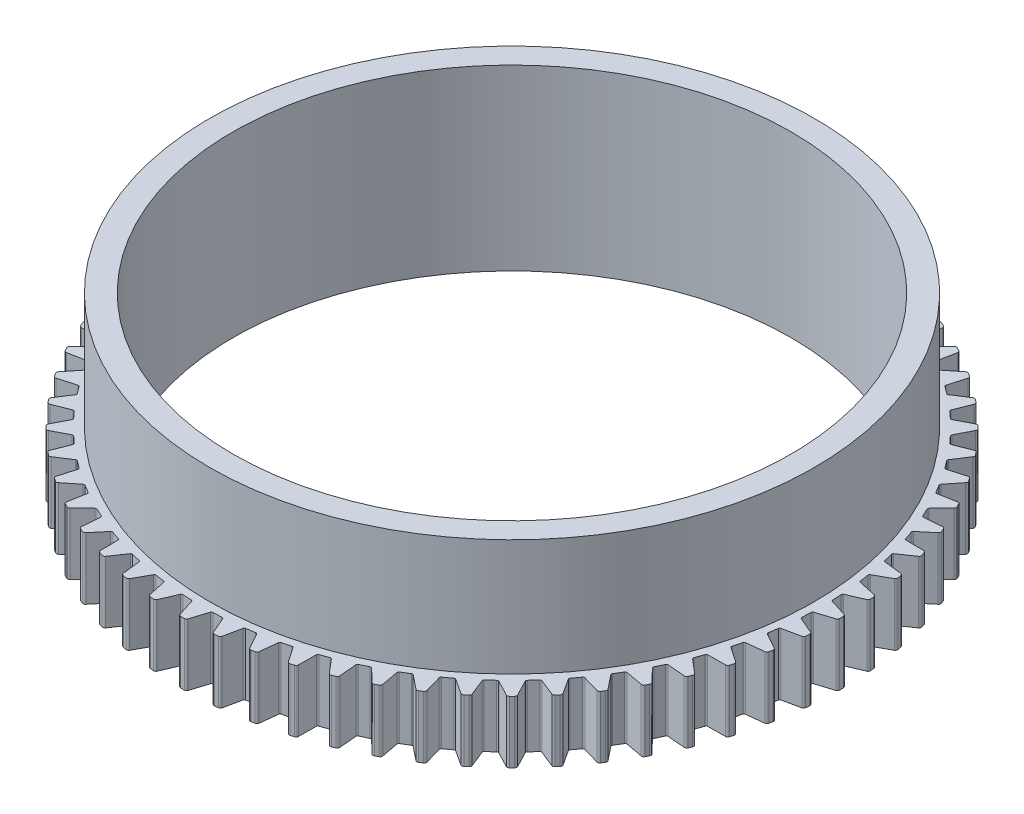
SolidWorks part; units mm, degrees
ref_plane "Front Plane" through (0, 0, 0) normal (0, 0, 1) x (1, 0, 0)
ref_plane "Top Plane" through (0, 0, 0) normal (0, 1, 0) x (1, 0, 0)
ref_plane "Right Plane" through (0, 0, 0) normal (1, 0, 0) x (0, 0, -1)
sketch "Sketch1" plane through (0, 0, 0) normal (0, 1, 0) x (1, 0, 0)
  line L0 (0, 53.7167) -> (0, -50.4595) construction
  line L1 (-0.5164, 42.2908) -> (-1.2072, 40.1152)
  line L2 (-0.2305, 42.5) -> (0.2305, 42.5)
  line L3 (0.5164, 42.2908) -> (1.2072, 40.1152)
  line L4 (3.6313, 42.1378) -> (2.7306, 40.0403)
  line L5 (4.6592, 42.0365) -> (5.1334, 39.8037)
  line L6 (3.9363, 42.3179) -> (4.3951, 42.2728)
  line L7 (7.744, 41.5789) -> (6.642, 39.5799)
  line L8 (8.757, 41.3774) -> (9.0101, 39.1088)
  line L9 (8.0653, 41.7283) -> (8.5174, 41.6384)
  line L10 (11.7822, 40.6197) -> (10.4896, 38.7383)
  line L11 (12.7706, 40.3199) -> (12.8001, 38.0374)
  line L12 (12.1165, 40.7369) -> (12.5577, 40.6031)
  line L13 (15.7069, 39.2692) -> (14.2361, 37.5236)
  line L14 (16.6611, 38.874) -> (16.4667, 36.5996)
  line L15 (16.0511, 39.3531) -> (16.477, 39.1767)
  line L16 (19.4803, 37.5406) -> (17.8455, 35.9475)
  line L17 (20.3912, 37.0537) -> (19.9748, 34.8093)
  line L18 (19.8311, 37.5903) -> (20.2376, 37.373)
  line L19 (23.0661, 35.4504) -> (21.283, 34.0252)
  line L20 (23.9249, 34.8766) -> (23.2906, 32.6838)
  line L21 (23.4201, 35.4655) -> (23.8034, 35.2094)
  line L22 (26.4298, 33.0188) -> (24.5156, 31.7753)
  line L23 (27.2282, 32.3636) -> (26.382, 30.2436)
  line L24 (26.7835, 32.9992) -> (27.1399, 32.7067)
  line L25 (29.5389, 30.2693) -> (27.5121, 29.2193)
  line L26 (30.2693, 29.5389) -> (29.2193, 27.5121)
  line L27 (29.8891, 30.215) -> (30.215, 29.8891)
  line L28 (32.3636, 27.2282) -> (30.2436, 26.382)
  line L29 (33.0188, 26.4298) -> (31.7753, 24.5156)
  line L30 (32.7067, 27.1399) -> (32.9992, 26.7835)
  line L31 (34.8766, 23.9249) -> (32.6838, 23.2906)
  line L32 (35.4504, 23.0661) -> (34.0252, 21.283)
  line L33 (35.2094, 23.8034) -> (35.4655, 23.4201)
  line L34 (37.0537, 20.3912) -> (34.8093, 19.9748)
  line L35 (37.5406, 19.4803) -> (35.9475, 17.8455)
  line L36 (37.373, 20.2376) -> (37.5903, 19.8311)
  line L37 (38.874, 16.6611) -> (36.5996, 16.4667)
  line L38 (39.2692, 15.7069) -> (37.5236, 14.2361)
  line L39 (39.1767, 16.477) -> (39.3531, 16.0511)
  line L40 (40.3199, 12.7706) -> (38.0374, 12.8001)
  line L41 (40.6197, 11.7822) -> (38.7383, 10.4896)
  line L42 (40.6031, 12.5577) -> (40.7369, 12.1165)
  line L43 (41.3774, 8.757) -> (39.1088, 9.0101)
  line L44 (41.5789, 7.744) -> (39.5799, 6.642)
  line L45 (41.6384, 8.5174) -> (41.7283, 8.0653)
  line L46 (42.0365, 4.6592) -> (39.8037, 5.1334)
  line L47 (42.1378, 3.6313) -> (40.0403, 2.7306)
  line L48 (42.2728, 4.3951) -> (42.3179, 3.9363)
  line L49 (42.2908, 0.5164) -> (40.1152, 1.2072)
  line L50 (42.2908, -0.5164) -> (40.1152, -1.2072)
  line L51 (42.5, 0.2305) -> (42.5, -0.2305)
  line L52 (42.1378, -3.6313) -> (40.0403, -2.7306)
  line L53 (42.0365, -4.6592) -> (39.8037, -5.1334)
  line L54 (42.3179, -3.9363) -> (42.2728, -4.3951)
  line L55 (41.5789, -7.744) -> (39.5799, -6.642)
  line L56 (41.3774, -8.757) -> (39.1088, -9.0101)
  line L57 (41.7283, -8.0653) -> (41.6384, -8.5174)
  line L58 (40.6197, -11.7822) -> (38.7383, -10.4896)
  line L59 (40.3199, -12.7706) -> (38.0374, -12.8001)
  line L60 (40.7369, -12.1165) -> (40.6031, -12.5577)
  line L61 (39.2692, -15.7069) -> (37.5236, -14.2361)
  line L62 (38.874, -16.6611) -> (36.5996, -16.4667)
  line L63 (39.3531, -16.0511) -> (39.1767, -16.477)
  line L64 (37.5406, -19.4803) -> (35.9475, -17.8455)
  line L65 (37.0537, -20.3912) -> (34.8093, -19.9748)
  line L66 (37.5903, -19.8311) -> (37.373, -20.2376)
  line L67 (35.4504, -23.0661) -> (34.0252, -21.283)
  line L68 (34.8766, -23.9249) -> (32.6838, -23.2906)
  line L69 (35.4655, -23.4201) -> (35.2094, -23.8034)
  line L70 (33.0188, -26.4298) -> (31.7753, -24.5156)
  line L71 (32.3636, -27.2282) -> (30.2436, -26.382)
  line L72 (32.9992, -26.7835) -> (32.7067, -27.1399)
  line L73 (30.2693, -29.5389) -> (29.2193, -27.5121)
  line L74 (29.5389, -30.2693) -> (27.5121, -29.2193)
  line L75 (30.215, -29.8891) -> (29.8891, -30.215)
  line L76 (27.2282, -32.3636) -> (26.382, -30.2436)
  line L77 (26.4298, -33.0188) -> (24.5156, -31.7753)
  line L78 (27.1399, -32.7067) -> (26.7835, -32.9992)
  line L79 (23.9249, -34.8766) -> (23.2906, -32.6838)
  line L80 (23.0661, -35.4504) -> (21.283, -34.0252)
  line L81 (23.8034, -35.2094) -> (23.4201, -35.4655)
  line L82 (20.3912, -37.0537) -> (19.9748, -34.8093)
  line L83 (19.4803, -37.5406) -> (17.8455, -35.9475)
  line L84 (20.2376, -37.373) -> (19.8311, -37.5903)
  line L85 (16.6611, -38.874) -> (16.4667, -36.5996)
  line L86 (15.7069, -39.2692) -> (14.2361, -37.5236)
  line L87 (16.477, -39.1767) -> (16.0511, -39.3531)
  line L88 (12.7706, -40.3199) -> (12.8001, -38.0374)
  line L89 (11.7822, -40.6197) -> (10.4896, -38.7383)
  line L90 (12.5577, -40.6031) -> (12.1165, -40.7369)
  line L91 (8.757, -41.3774) -> (9.0101, -39.1088)
  line L92 (7.744, -41.5789) -> (6.642, -39.5799)
  line L93 (8.5174, -41.6384) -> (8.0653, -41.7283)
  line L94 (4.6592, -42.0365) -> (5.1334, -39.8037)
  line L95 (3.6313, -42.1378) -> (2.7306, -40.0403)
  line L96 (4.3951, -42.2728) -> (3.9363, -42.3179)
  line L97 (0.5164, -42.2908) -> (1.2072, -40.1152)
  line L98 (-0.5164, -42.2908) -> (-1.2072, -40.1152)
  line L99 (0.2305, -42.5) -> (-0.2305, -42.5)
  line L100 (-3.6313, -42.1378) -> (-2.7306, -40.0403)
  line L101 (-4.6592, -42.0365) -> (-5.1334, -39.8037)
  line L102 (-3.9363, -42.3179) -> (-4.3951, -42.2728)
  line L103 (-7.744, -41.5789) -> (-6.642, -39.5799)
  line L104 (-8.757, -41.3774) -> (-9.0101, -39.1088)
  line L105 (-8.0653, -41.7283) -> (-8.5174, -41.6384)
  line L106 (-11.7822, -40.6197) -> (-10.4896, -38.7383)
  line L107 (-12.7706, -40.3199) -> (-12.8001, -38.0374)
  line L108 (-12.1165, -40.7369) -> (-12.5577, -40.6031)
  line L109 (-15.7069, -39.2692) -> (-14.2361, -37.5236)
  line L110 (-16.6611, -38.874) -> (-16.4667, -36.5996)
  line L111 (-16.0511, -39.3531) -> (-16.477, -39.1767)
  line L112 (-19.4803, -37.5406) -> (-17.8455, -35.9475)
  line L113 (-20.3912, -37.0537) -> (-19.9748, -34.8093)
  line L114 (-19.8311, -37.5903) -> (-20.2376, -37.373)
  line L115 (-23.0661, -35.4504) -> (-21.283, -34.0252)
  line L116 (-23.9249, -34.8766) -> (-23.2906, -32.6838)
  line L117 (-23.4201, -35.4655) -> (-23.8034, -35.2094)
  line L118 (-26.4298, -33.0188) -> (-24.5156, -31.7753)
  line L119 (-27.2282, -32.3636) -> (-26.382, -30.2436)
  line L120 (-26.7835, -32.9992) -> (-27.1399, -32.7067)
  line L121 (-29.5389, -30.2693) -> (-27.5121, -29.2193)
  line L122 (-30.2693, -29.5389) -> (-29.2193, -27.5121)
  line L123 (-29.8891, -30.215) -> (-30.215, -29.8891)
  line L124 (-32.3636, -27.2282) -> (-30.2436, -26.382)
  line L125 (-33.0188, -26.4298) -> (-31.7753, -24.5156)
  line L126 (-32.7067, -27.1399) -> (-32.9992, -26.7835)
  line L127 (-34.8766, -23.9249) -> (-32.6838, -23.2906)
  line L128 (-35.4504, -23.0661) -> (-34.0252, -21.283)
  line L129 (-35.2094, -23.8034) -> (-35.4655, -23.4201)
  line L130 (-37.0537, -20.3912) -> (-34.8093, -19.9748)
  line L131 (-37.5406, -19.4803) -> (-35.9475, -17.8455)
  line L132 (-37.373, -20.2376) -> (-37.5903, -19.8311)
  line L133 (-38.874, -16.6611) -> (-36.5996, -16.4667)
  line L134 (-39.2692, -15.7069) -> (-37.5236, -14.2361)
  line L135 (-39.1767, -16.477) -> (-39.3531, -16.0511)
  line L136 (-40.3199, -12.7706) -> (-38.0374, -12.8001)
  line L137 (-40.6197, -11.7822) -> (-38.7383, -10.4896)
  line L138 (-40.6031, -12.5577) -> (-40.7369, -12.1165)
  line L139 (-41.3774, -8.757) -> (-39.1088, -9.0101)
  line L140 (-41.5789, -7.744) -> (-39.5799, -6.642)
  line L141 (-41.6384, -8.5174) -> (-41.7283, -8.0653)
  line L142 (-42.0365, -4.6592) -> (-39.8037, -5.1334)
  line L143 (-42.1378, -3.6313) -> (-40.0403, -2.7306)
  line L144 (-42.2728, -4.3951) -> (-42.3179, -3.9363)
  line L145 (-42.2908, -0.5164) -> (-40.1152, -1.2072)
  line L146 (-42.2908, 0.5164) -> (-40.1152, 1.2072)
  line L147 (-42.5, -0.2305) -> (-42.5, 0.2305)
  line L148 (-42.1378, 3.6313) -> (-40.0403, 2.7306)
  line L149 (-42.0365, 4.6592) -> (-39.8037, 5.1334)
  line L150 (-42.3179, 3.9363) -> (-42.2728, 4.3951)
  line L151 (-41.5789, 7.744) -> (-39.5799, 6.642)
  line L152 (-41.3774, 8.757) -> (-39.1088, 9.0101)
  line L153 (-41.7283, 8.0653) -> (-41.6384, 8.5174)
  line L154 (-40.6197, 11.7822) -> (-38.7383, 10.4896)
  line L155 (-40.3199, 12.7706) -> (-38.0374, 12.8001)
  line L156 (-40.7369, 12.1165) -> (-40.6031, 12.5577)
  line L157 (-39.2692, 15.7069) -> (-37.5236, 14.2361)
  line L158 (-38.874, 16.6611) -> (-36.5996, 16.4667)
  line L159 (-39.3531, 16.0511) -> (-39.1767, 16.477)
  line L160 (-37.5406, 19.4803) -> (-35.9475, 17.8455)
  line L161 (-37.0537, 20.3912) -> (-34.8093, 19.9748)
  line L162 (-37.5903, 19.8311) -> (-37.373, 20.2376)
  line L163 (-35.4504, 23.0661) -> (-34.0252, 21.283)
  line L164 (-34.8766, 23.9249) -> (-32.6838, 23.2906)
  line L165 (-35.4655, 23.4201) -> (-35.2094, 23.8034)
  line L166 (-33.0188, 26.4298) -> (-31.7753, 24.5156)
  line L167 (-32.3636, 27.2282) -> (-30.2436, 26.382)
  line L168 (-32.9992, 26.7835) -> (-32.7067, 27.1399)
  line L169 (-30.2693, 29.5389) -> (-29.2193, 27.5121)
  line L170 (-29.5389, 30.2693) -> (-27.5121, 29.2193)
  line L171 (-30.215, 29.8891) -> (-29.8891, 30.215)
  line L172 (-27.2282, 32.3636) -> (-26.382, 30.2436)
  line L173 (-26.4298, 33.0188) -> (-24.5156, 31.7753)
  line L174 (-27.1399, 32.7067) -> (-26.7835, 32.9992)
  line L175 (-23.9249, 34.8766) -> (-23.2906, 32.6838)
  line L176 (-23.0661, 35.4504) -> (-21.283, 34.0252)
  line L177 (-23.8034, 35.2094) -> (-23.4201, 35.4655)
  line L178 (-20.3912, 37.0537) -> (-19.9748, 34.8093)
  line L179 (-19.4803, 37.5406) -> (-17.8455, 35.9475)
  line L180 (-20.2376, 37.373) -> (-19.8311, 37.5903)
  line L181 (-16.6611, 38.874) -> (-16.4667, 36.5996)
  line L182 (-15.7069, 39.2692) -> (-14.2361, 37.5236)
  line L183 (-16.477, 39.1767) -> (-16.0511, 39.3531)
  line L184 (-12.7706, 40.3199) -> (-12.8001, 38.0374)
  line L185 (-11.7822, 40.6197) -> (-10.4896, 38.7383)
  line L186 (-12.5577, 40.6031) -> (-12.1165, 40.7369)
  line L187 (-8.757, 41.3774) -> (-9.0101, 39.1088)
  line L188 (-7.744, 41.5789) -> (-6.642, 39.5799)
  line L189 (-8.5174, 41.6384) -> (-8.0653, 41.7283)
  line L190 (-4.6592, 42.0365) -> (-5.1334, 39.8037)
  line L191 (-3.6313, 42.1378) -> (-2.7306, 40.0403)
  line L192 (-4.3951, 42.2728) -> (-3.9363, 42.3179)
  arc A0 (-1.3909, 39.9758) -> (-2.5341, 39.9196) centre (0, 0) ccw
  arc A1 (-0.5164, 42.2908) -> (-0.2305, 42.5) centre (-0.2305, 42.2) cw
  arc A2 (0.2305, 42.5) -> (0.5164, 42.2908) centre (0.2305, 42.2) cw
  arc A3 (1.2072, 40.1152) -> (1.3909, 39.9758) centre (1.3979, 40.1757) ccw
  arc A4 (-1.2072, 40.1152) -> (-1.3909, 39.9758) centre (-1.3979, 40.1757) cw
  arc A5 (2.7306, 40.0403) -> (2.5341, 39.9196) centre (2.5468, 40.1192) cw
  arc A6 (5.1334, 39.8037) -> (5.3025, 39.647) centre (5.329, 39.8452) ccw
  arc A7 (4.3951, 42.2728) -> (4.6592, 42.0365) centre (4.3657, 41.9742) cw
  arc A8 (3.6313, 42.1378) -> (3.9363, 42.3179) centre (3.9069, 42.0194) cw
  arc A9 (6.642, 39.5799) -> (6.4347, 39.479) centre (6.4669, 39.6764) cw
  arc A10 (9.0101, 39.1088) -> (9.1631, 38.9363) centre (9.2089, 39.131) ccw
  arc A11 (8.5174, 41.6384) -> (8.757, 41.3774) centre (8.4589, 41.3442) cw
  arc A12 (7.744, 41.5789) -> (8.0653, 41.7283) centre (8.0067, 41.4341) cw
  arc A13 (10.4896, 38.7383) -> (10.2734, 38.6582) centre (10.3247, 38.8515) cw
  arc A14 (12.8001, 38.0374) -> (12.9354, 37.8507) centre (13, 38.04) ccw
  arc A15 (12.5577, 40.6031) -> (12.7706, 40.3199) centre (12.4706, 40.316) cw
  arc A16 (11.7822, 40.6197) -> (12.1165, 40.7369) centre (12.0294, 40.4498) cw
  arc A17 (14.2361, 37.5236) -> (14.0131, 37.4651) centre (14.0831, 37.6524) cw
  arc A18 (16.4667, 36.5996) -> (16.5831, 36.4006) centre (16.666, 36.5826) ccw
  arc A19 (16.477, 39.1767) -> (16.6611, 38.874) centre (16.3622, 38.8995) cw
  arc A20 (15.7069, 39.2692) -> (16.0511, 39.3531) centre (15.9363, 39.0759) cw
  arc A21 (17.8455, 35.9475) -> (17.6178, 35.9112) centre (17.7059, 36.0907) cw
  arc A22 (19.9748, 34.8093) -> (20.0711, 34.5999) centre (20.1715, 34.7729) ccw
  arc A23 (20.2376, 37.373) -> (20.3912, 37.0537) centre (20.0962, 37.1084) cw
  arc A24 (19.4803, 37.5406) -> (19.8311, 37.5903) centre (19.6897, 37.3257) cw
  arc A25 (21.283, 34.0252) -> (21.0529, 34.0114) centre (21.1581, 34.1815) cw
  arc A26 (23.2906, 32.6838) -> (23.3659, 32.4659) centre (23.4827, 32.6283) ccw
  arc A27 (23.8034, 35.2094) -> (23.9249, 34.8766) centre (23.6367, 34.96) cw
  arc A28 (23.0661, 35.4504) -> (23.4201, 35.4655) centre (23.2534, 35.2161) cw
  arc A29 (24.5156, 31.7753) -> (24.2852, 31.7841) centre (24.4066, 31.943) cw
  arc A30 (26.382, 30.2436) -> (26.4356, 30.0193) centre (26.5677, 30.1694) ccw
  arc A31 (27.1399, 32.7067) -> (27.2282, 32.3636) centre (26.9496, 32.4748) cw
  arc A32 (26.4298, 33.0188) -> (26.7835, 32.9992) centre (26.5932, 32.7673) cw
  arc A33 (27.5121, 29.2193) -> (27.2837, 29.2507) centre (27.4201, 29.3969) cw
  arc A34 (29.2193, 27.5121) -> (29.2507, 27.2837) centre (29.3969, 27.4201) ccw
  arc A35 (30.215, 29.8891) -> (30.2693, 29.5389) centre (30.0029, 29.6769) cw
  arc A36 (29.5389, 30.2693) -> (29.8891, 30.215) centre (29.6769, 30.0029) cw
  arc A37 (30.2436, 26.382) -> (30.0193, 26.4356) centre (30.1694, 26.5677) cw
  arc A38 (31.7753, 24.5156) -> (31.7841, 24.2852) centre (31.943, 24.4066) ccw
  arc A39 (32.9992, 26.7835) -> (33.0188, 26.4298) centre (32.7673, 26.5932) cw
  arc A40 (32.3636, 27.2282) -> (32.7067, 27.1399) centre (32.4748, 26.9496) cw
  arc A41 (32.6838, 23.2906) -> (32.4659, 23.3659) centre (32.6283, 23.4827) cw
  arc A42 (34.0252, 21.283) -> (34.0114, 21.0529) centre (34.1815, 21.1581) ccw
  arc A43 (35.4655, 23.4201) -> (35.4504, 23.0661) centre (35.2161, 23.2534) cw
  arc A44 (34.8766, 23.9249) -> (35.2094, 23.8034) centre (34.96, 23.6367) cw
  arc A45 (34.8093, 19.9748) -> (34.5999, 20.0711) centre (34.7729, 20.1715) cw
  arc A46 (35.9475, 17.8455) -> (35.9112, 17.6178) centre (36.0907, 17.7059) ccw
  arc A47 (37.5903, 19.8311) -> (37.5406, 19.4803) centre (37.3257, 19.6897) cw
  arc A48 (37.0537, 20.3912) -> (37.373, 20.2376) centre (37.1084, 20.0962) cw
  arc A49 (36.5996, 16.4667) -> (36.4006, 16.5831) centre (36.5826, 16.666) cw
  arc A50 (37.5236, 14.2361) -> (37.4651, 14.0131) centre (37.6524, 14.0831) ccw
  arc A51 (39.3531, 16.0511) -> (39.2692, 15.7069) centre (39.0759, 15.9363) cw
  arc A52 (38.874, 16.6611) -> (39.1767, 16.477) centre (38.8995, 16.3622) cw
  arc A53 (38.0374, 12.8001) -> (37.8507, 12.9354) centre (38.04, 13) cw
  arc A54 (38.7383, 10.4896) -> (38.6582, 10.2734) centre (38.8515, 10.3247) ccw
  arc A55 (40.7369, 12.1165) -> (40.6197, 11.7822) centre (40.4498, 12.0294) cw
  arc A56 (40.3199, 12.7706) -> (40.6031, 12.5577) centre (40.316, 12.4706) cw
  arc A57 (39.1088, 9.0101) -> (38.9363, 9.1631) centre (39.131, 9.2089) cw
  arc A58 (39.5799, 6.642) -> (39.479, 6.4347) centre (39.6764, 6.4669) ccw
  arc A59 (41.7283, 8.0653) -> (41.5789, 7.744) centre (41.4341, 8.0067) cw
  arc A60 (41.3774, 8.757) -> (41.6384, 8.5174) centre (41.3442, 8.4589) cw
  arc A61 (39.8037, 5.1334) -> (39.647, 5.3025) centre (39.8452, 5.329) cw
  arc A62 (40.0403, 2.7306) -> (39.9196, 2.5341) centre (40.1192, 2.5468) ccw
  arc A63 (42.3179, 3.9363) -> (42.1378, 3.6313) centre (42.0194, 3.9069) cw
  arc A64 (42.0365, 4.6592) -> (42.2728, 4.3951) centre (41.9742, 4.3657) cw
  arc A65 (40.1152, 1.2072) -> (39.9758, 1.3909) centre (40.1757, 1.3979) cw
  arc A66 (40.1152, -1.2072) -> (39.9758, -1.3909) centre (40.1757, -1.3979) ccw
  arc A67 (42.5, -0.2305) -> (42.2908, -0.5164) centre (42.2, -0.2305) cw
  arc A68 (42.2908, 0.5164) -> (42.5, 0.2305) centre (42.2, 0.2305) cw
  arc A69 (40.0403, -2.7306) -> (39.9196, -2.5341) centre (40.1192, -2.5468) cw
  arc A70 (39.8037, -5.1334) -> (39.647, -5.3025) centre (39.8452, -5.329) ccw
  arc A71 (42.2728, -4.3951) -> (42.0365, -4.6592) centre (41.9742, -4.3657) cw
  arc A72 (42.1378, -3.6313) -> (42.3179, -3.9363) centre (42.0194, -3.9069) cw
  arc A73 (39.5799, -6.642) -> (39.479, -6.4347) centre (39.6764, -6.4669) cw
  arc A74 (39.1088, -9.0101) -> (38.9363, -9.1631) centre (39.131, -9.2089) ccw
  arc A75 (41.6384, -8.5174) -> (41.3774, -8.757) centre (41.3442, -8.4589) cw
  arc A76 (41.5789, -7.744) -> (41.7283, -8.0653) centre (41.4341, -8.0067) cw
  arc A77 (38.7383, -10.4896) -> (38.6582, -10.2734) centre (38.8515, -10.3247) cw
  arc A78 (38.0374, -12.8001) -> (37.8507, -12.9354) centre (38.04, -13) ccw
  arc A79 (40.6031, -12.5577) -> (40.3199, -12.7706) centre (40.316, -12.4706) cw
  arc A80 (40.6197, -11.7822) -> (40.7369, -12.1165) centre (40.4498, -12.0294) cw
  arc A81 (37.5236, -14.2361) -> (37.4651, -14.0131) centre (37.6524, -14.0831) cw
  arc A82 (36.5996, -16.4667) -> (36.4006, -16.5831) centre (36.5826, -16.666) ccw
  arc A83 (39.1767, -16.477) -> (38.874, -16.6611) centre (38.8995, -16.3622) cw
  arc A84 (39.2692, -15.7069) -> (39.3531, -16.0511) centre (39.0759, -15.9363) cw
  arc A85 (35.9475, -17.8455) -> (35.9112, -17.6178) centre (36.0907, -17.7059) cw
  arc A86 (34.8093, -19.9748) -> (34.5999, -20.0711) centre (34.7729, -20.1715) ccw
  arc A87 (37.373, -20.2376) -> (37.0537, -20.3912) centre (37.1084, -20.0962) cw
  arc A88 (37.5406, -19.4803) -> (37.5903, -19.8311) centre (37.3257, -19.6897) cw
  arc A89 (34.0252, -21.283) -> (34.0114, -21.0529) centre (34.1815, -21.1581) cw
  arc A90 (32.6838, -23.2906) -> (32.4659, -23.3659) centre (32.6283, -23.4827) ccw
  arc A91 (35.2094, -23.8034) -> (34.8766, -23.9249) centre (34.96, -23.6367) cw
  arc A92 (35.4504, -23.0661) -> (35.4655, -23.4201) centre (35.2161, -23.2534) cw
  arc A93 (31.7753, -24.5156) -> (31.7841, -24.2852) centre (31.943, -24.4066) cw
  arc A94 (30.2436, -26.382) -> (30.0193, -26.4356) centre (30.1694, -26.5677) ccw
  arc A95 (32.7067, -27.1399) -> (32.3636, -27.2282) centre (32.4748, -26.9496) cw
  arc A96 (33.0188, -26.4298) -> (32.9992, -26.7835) centre (32.7673, -26.5932) cw
  arc A97 (29.2193, -27.5121) -> (29.2507, -27.2837) centre (29.3969, -27.4201) cw
  arc A98 (27.5121, -29.2193) -> (27.2837, -29.2507) centre (27.4201, -29.3969) ccw
  arc A99 (29.8891, -30.215) -> (29.5389, -30.2693) centre (29.6769, -30.0029) cw
  arc A100 (30.2693, -29.5389) -> (30.215, -29.8891) centre (30.0029, -29.6769) cw
  arc A101 (26.382, -30.2436) -> (26.4356, -30.0193) centre (26.5677, -30.1694) cw
  arc A102 (24.5156, -31.7753) -> (24.2852, -31.7841) centre (24.4066, -31.943) ccw
  arc A103 (26.7835, -32.9992) -> (26.4298, -33.0188) centre (26.5932, -32.7673) cw
  arc A104 (27.2282, -32.3636) -> (27.1399, -32.7067) centre (26.9496, -32.4748) cw
  arc A105 (23.2906, -32.6838) -> (23.3659, -32.4659) centre (23.4827, -32.6283) cw
  arc A106 (21.283, -34.0252) -> (21.0529, -34.0114) centre (21.1581, -34.1815) ccw
  arc A107 (23.4201, -35.4655) -> (23.0661, -35.4504) centre (23.2534, -35.2161) cw
  arc A108 (23.9249, -34.8766) -> (23.8034, -35.2094) centre (23.6367, -34.96) cw
  arc A109 (19.9748, -34.8093) -> (20.0711, -34.5999) centre (20.1715, -34.7729) cw
  arc A110 (17.8455, -35.9475) -> (17.6178, -35.9112) centre (17.7059, -36.0907) ccw
  arc A111 (19.8311, -37.5903) -> (19.4803, -37.5406) centre (19.6897, -37.3257) cw
  arc A112 (20.3912, -37.0537) -> (20.2376, -37.373) centre (20.0962, -37.1084) cw
  arc A113 (16.4667, -36.5996) -> (16.5831, -36.4006) centre (16.666, -36.5826) cw
  arc A114 (14.2361, -37.5236) -> (14.0131, -37.4651) centre (14.0831, -37.6524) ccw
  arc A115 (16.0511, -39.3531) -> (15.7069, -39.2692) centre (15.9363, -39.0759) cw
  arc A116 (16.6611, -38.874) -> (16.477, -39.1767) centre (16.3622, -38.8995) cw
  arc A117 (12.8001, -38.0374) -> (12.9354, -37.8507) centre (13, -38.04) cw
  arc A118 (10.4896, -38.7383) -> (10.2734, -38.6582) centre (10.3247, -38.8515) ccw
  arc A119 (12.1165, -40.7369) -> (11.7822, -40.6197) centre (12.0294, -40.4498) cw
  arc A120 (12.7706, -40.3199) -> (12.5577, -40.6031) centre (12.4706, -40.316) cw
  arc A121 (9.0101, -39.1088) -> (9.1631, -38.9363) centre (9.2089, -39.131) cw
  arc A122 (6.642, -39.5799) -> (6.4347, -39.479) centre (6.4669, -39.6764) ccw
  arc A123 (8.0653, -41.7283) -> (7.744, -41.5789) centre (8.0067, -41.4341) cw
  arc A124 (8.757, -41.3774) -> (8.5174, -41.6384) centre (8.4589, -41.3442) cw
  arc A125 (5.1334, -39.8037) -> (5.3025, -39.647) centre (5.329, -39.8452) cw
  arc A126 (2.7306, -40.0403) -> (2.5341, -39.9196) centre (2.5468, -40.1192) ccw
  arc A127 (3.9363, -42.3179) -> (3.6313, -42.1378) centre (3.9069, -42.0194) cw
  arc A128 (4.6592, -42.0365) -> (4.3951, -42.2728) centre (4.3657, -41.9742) cw
  arc A129 (1.2072, -40.1152) -> (1.3909, -39.9758) centre (1.3979, -40.1757) cw
  arc A130 (-1.2072, -40.1152) -> (-1.3909, -39.9758) centre (-1.3979, -40.1757) ccw
  arc A131 (-0.2305, -42.5) -> (-0.5164, -42.2908) centre (-0.2305, -42.2) cw
  arc A132 (0.5164, -42.2908) -> (0.2305, -42.5) centre (0.2305, -42.2) cw
  arc A133 (-2.7306, -40.0403) -> (-2.5341, -39.9196) centre (-2.5468, -40.1192) cw
  arc A134 (-5.1334, -39.8037) -> (-5.3025, -39.647) centre (-5.329, -39.8452) ccw
  arc A135 (-4.3951, -42.2728) -> (-4.6592, -42.0365) centre (-4.3657, -41.9742) cw
  arc A136 (-3.6313, -42.1378) -> (-3.9363, -42.3179) centre (-3.9069, -42.0194) cw
  arc A137 (-6.642, -39.5799) -> (-6.4347, -39.479) centre (-6.4669, -39.6764) cw
  arc A138 (-9.0101, -39.1088) -> (-9.1631, -38.9363) centre (-9.2089, -39.131) ccw
  arc A139 (-8.5174, -41.6384) -> (-8.757, -41.3774) centre (-8.4589, -41.3442) cw
  arc A140 (-7.744, -41.5789) -> (-8.0653, -41.7283) centre (-8.0067, -41.4341) cw
  arc A141 (-10.4896, -38.7383) -> (-10.2734, -38.6582) centre (-10.3247, -38.8515) cw
  arc A142 (-12.8001, -38.0374) -> (-12.9354, -37.8507) centre (-13, -38.04) ccw
  arc A143 (-12.5577, -40.6031) -> (-12.7706, -40.3199) centre (-12.4706, -40.316) cw
  arc A144 (-11.7822, -40.6197) -> (-12.1165, -40.7369) centre (-12.0294, -40.4498) cw
  arc A145 (-14.2361, -37.5236) -> (-14.0131, -37.4651) centre (-14.0831, -37.6524) cw
  arc A146 (-16.4667, -36.5996) -> (-16.5831, -36.4006) centre (-16.666, -36.5826) ccw
  arc A147 (-16.477, -39.1767) -> (-16.6611, -38.874) centre (-16.3622, -38.8995) cw
  arc A148 (-15.7069, -39.2692) -> (-16.0511, -39.3531) centre (-15.9363, -39.0759) cw
  arc A149 (-17.8455, -35.9475) -> (-17.6178, -35.9112) centre (-17.7059, -36.0907) cw
  arc A150 (-19.9748, -34.8093) -> (-20.0711, -34.5999) centre (-20.1715, -34.7729) ccw
  arc A151 (-20.2376, -37.373) -> (-20.3912, -37.0537) centre (-20.0962, -37.1084) cw
  arc A152 (-19.4803, -37.5406) -> (-19.8311, -37.5903) centre (-19.6897, -37.3257) cw
  arc A153 (-21.283, -34.0252) -> (-21.0529, -34.0114) centre (-21.1581, -34.1815) cw
  arc A154 (-23.2906, -32.6838) -> (-23.3659, -32.4659) centre (-23.4827, -32.6283) ccw
  arc A155 (-23.8034, -35.2094) -> (-23.9249, -34.8766) centre (-23.6367, -34.96) cw
  arc A156 (-23.0661, -35.4504) -> (-23.4201, -35.4655) centre (-23.2534, -35.2161) cw
  arc A157 (-24.5156, -31.7753) -> (-24.2852, -31.7841) centre (-24.4066, -31.943) cw
  arc A158 (-26.382, -30.2436) -> (-26.4356, -30.0193) centre (-26.5677, -30.1694) ccw
  arc A159 (-27.1399, -32.7067) -> (-27.2282, -32.3636) centre (-26.9496, -32.4748) cw
  arc A160 (-26.4298, -33.0188) -> (-26.7835, -32.9992) centre (-26.5932, -32.7673) cw
  arc A161 (-27.5121, -29.2193) -> (-27.2837, -29.2507) centre (-27.4201, -29.3969) cw
  arc A162 (-29.2193, -27.5121) -> (-29.2507, -27.2837) centre (-29.3969, -27.4201) ccw
  arc A163 (-30.215, -29.8891) -> (-30.2693, -29.5389) centre (-30.0029, -29.6769) cw
  arc A164 (-29.5389, -30.2693) -> (-29.8891, -30.215) centre (-29.6769, -30.0029) cw
  arc A165 (-30.2436, -26.382) -> (-30.0193, -26.4356) centre (-30.1694, -26.5677) cw
  arc A166 (-31.7753, -24.5156) -> (-31.7841, -24.2852) centre (-31.943, -24.4066) ccw
  arc A167 (-32.9992, -26.7835) -> (-33.0188, -26.4298) centre (-32.7673, -26.5932) cw
  arc A168 (-32.3636, -27.2282) -> (-32.7067, -27.1399) centre (-32.4748, -26.9496) cw
  arc A169 (-32.6838, -23.2906) -> (-32.4659, -23.3659) centre (-32.6283, -23.4827) cw
  arc A170 (-34.0252, -21.283) -> (-34.0114, -21.0529) centre (-34.1815, -21.1581) ccw
  arc A171 (-35.4655, -23.4201) -> (-35.4504, -23.0661) centre (-35.2161, -23.2534) cw
  arc A172 (-34.8766, -23.9249) -> (-35.2094, -23.8034) centre (-34.96, -23.6367) cw
  arc A173 (-34.8093, -19.9748) -> (-34.5999, -20.0711) centre (-34.7729, -20.1715) cw
  arc A174 (-35.9475, -17.8455) -> (-35.9112, -17.6178) centre (-36.0907, -17.7059) ccw
  arc A175 (-37.5903, -19.8311) -> (-37.5406, -19.4803) centre (-37.3257, -19.6897) cw
  arc A176 (-37.0537, -20.3912) -> (-37.373, -20.2376) centre (-37.1084, -20.0962) cw
  arc A177 (-36.5996, -16.4667) -> (-36.4006, -16.5831) centre (-36.5826, -16.666) cw
  arc A178 (-37.5236, -14.2361) -> (-37.4651, -14.0131) centre (-37.6524, -14.0831) ccw
  arc A179 (-39.3531, -16.0511) -> (-39.2692, -15.7069) centre (-39.0759, -15.9363) cw
  arc A180 (-38.874, -16.6611) -> (-39.1767, -16.477) centre (-38.8995, -16.3622) cw
  arc A181 (-38.0374, -12.8001) -> (-37.8507, -12.9354) centre (-38.04, -13) cw
  arc A182 (-38.7383, -10.4896) -> (-38.6582, -10.2734) centre (-38.8515, -10.3247) ccw
  arc A183 (-40.7369, -12.1165) -> (-40.6197, -11.7822) centre (-40.4498, -12.0294) cw
  arc A184 (-40.3199, -12.7706) -> (-40.6031, -12.5577) centre (-40.316, -12.4706) cw
  arc A185 (-39.1088, -9.0101) -> (-38.9363, -9.1631) centre (-39.131, -9.2089) cw
  arc A186 (-39.5799, -6.642) -> (-39.479, -6.4347) centre (-39.6764, -6.4669) ccw
  arc A187 (-41.7283, -8.0653) -> (-41.5789, -7.744) centre (-41.4341, -8.0067) cw
  arc A188 (-41.3774, -8.757) -> (-41.6384, -8.5174) centre (-41.3442, -8.4589) cw
  arc A189 (-39.8037, -5.1334) -> (-39.647, -5.3025) centre (-39.8452, -5.329) cw
  arc A190 (-40.0403, -2.7306) -> (-39.9196, -2.5341) centre (-40.1192, -2.5468) ccw
  arc A191 (-42.3179, -3.9363) -> (-42.1378, -3.6313) centre (-42.0194, -3.9069) cw
  arc A192 (-42.0365, -4.6592) -> (-42.2728, -4.3951) centre (-41.9742, -4.3657) cw
  arc A193 (-40.1152, -1.2072) -> (-39.9758, -1.3909) centre (-40.1757, -1.3979) cw
  arc A194 (-40.1152, 1.2072) -> (-39.9758, 1.3909) centre (-40.1757, 1.3979) ccw
  arc A195 (-42.5, 0.2305) -> (-42.2908, 0.5164) centre (-42.2, 0.2305) cw
  arc A196 (-42.2908, -0.5164) -> (-42.5, -0.2305) centre (-42.2, -0.2305) cw
  arc A197 (-40.0403, 2.7306) -> (-39.9196, 2.5341) centre (-40.1192, 2.5468) cw
  arc A198 (-39.8037, 5.1334) -> (-39.647, 5.3025) centre (-39.8452, 5.329) ccw
  arc A199 (-42.2728, 4.3951) -> (-42.0365, 4.6592) centre (-41.9742, 4.3657) cw
  arc A200 (-42.1378, 3.6313) -> (-42.3179, 3.9363) centre (-42.0194, 3.9069) cw
  arc A201 (-39.5799, 6.642) -> (-39.479, 6.4347) centre (-39.6764, 6.4669) cw
  arc A202 (-39.1088, 9.0101) -> (-38.9363, 9.1631) centre (-39.131, 9.2089) ccw
  arc A203 (-41.6384, 8.5174) -> (-41.3774, 8.757) centre (-41.3442, 8.4589) cw
  arc A204 (-41.5789, 7.744) -> (-41.7283, 8.0653) centre (-41.4341, 8.0067) cw
  arc A205 (-38.7383, 10.4896) -> (-38.6582, 10.2734) centre (-38.8515, 10.3247) cw
  arc A206 (-38.0374, 12.8001) -> (-37.8507, 12.9354) centre (-38.04, 13) ccw
  arc A207 (-40.6031, 12.5577) -> (-40.3199, 12.7706) centre (-40.316, 12.4706) cw
  arc A208 (-40.6197, 11.7822) -> (-40.7369, 12.1165) centre (-40.4498, 12.0294) cw
  arc A209 (-37.5236, 14.2361) -> (-37.4651, 14.0131) centre (-37.6524, 14.0831) cw
  arc A210 (-36.5996, 16.4667) -> (-36.4006, 16.5831) centre (-36.5826, 16.666) ccw
  arc A211 (-39.1767, 16.477) -> (-38.874, 16.6611) centre (-38.8995, 16.3622) cw
  arc A212 (-39.2692, 15.7069) -> (-39.3531, 16.0511) centre (-39.0759, 15.9363) cw
  arc A213 (-35.9475, 17.8455) -> (-35.9112, 17.6178) centre (-36.0907, 17.7059) cw
  arc A214 (-34.8093, 19.9748) -> (-34.5999, 20.0711) centre (-34.7729, 20.1715) ccw
  arc A215 (-37.373, 20.2376) -> (-37.0537, 20.3912) centre (-37.1084, 20.0962) cw
  arc A216 (-37.5406, 19.4803) -> (-37.5903, 19.8311) centre (-37.3257, 19.6897) cw
  arc A217 (-34.0252, 21.283) -> (-34.0114, 21.0529) centre (-34.1815, 21.1581) cw
  arc A218 (-32.6838, 23.2906) -> (-32.4659, 23.3659) centre (-32.6283, 23.4827) ccw
  arc A219 (-35.2094, 23.8034) -> (-34.8766, 23.9249) centre (-34.96, 23.6367) cw
  arc A220 (-35.4504, 23.0661) -> (-35.4655, 23.4201) centre (-35.2161, 23.2534) cw
  arc A221 (-31.7753, 24.5156) -> (-31.7841, 24.2852) centre (-31.943, 24.4066) cw
  arc A222 (-30.2436, 26.382) -> (-30.0193, 26.4356) centre (-30.1694, 26.5677) ccw
  arc A223 (-32.7067, 27.1399) -> (-32.3636, 27.2282) centre (-32.4748, 26.9496) cw
  arc A224 (-33.0188, 26.4298) -> (-32.9992, 26.7835) centre (-32.7673, 26.5932) cw
  arc A225 (-29.2193, 27.5121) -> (-29.2507, 27.2837) centre (-29.3969, 27.4201) cw
  arc A226 (-27.5121, 29.2193) -> (-27.2837, 29.2507) centre (-27.4201, 29.3969) ccw
  arc A227 (-29.8891, 30.215) -> (-29.5389, 30.2693) centre (-29.6769, 30.0029) cw
  arc A228 (-30.2693, 29.5389) -> (-30.215, 29.8891) centre (-30.0029, 29.6769) cw
  arc A229 (-26.382, 30.2436) -> (-26.4356, 30.0193) centre (-26.5677, 30.1694) cw
  arc A230 (-24.5156, 31.7753) -> (-24.2852, 31.7841) centre (-24.4066, 31.943) ccw
  arc A231 (-26.7835, 32.9992) -> (-26.4298, 33.0188) centre (-26.5932, 32.7673) cw
  arc A232 (-27.2282, 32.3636) -> (-27.1399, 32.7067) centre (-26.9496, 32.4748) cw
  arc A233 (-23.2906, 32.6838) -> (-23.3659, 32.4659) centre (-23.4827, 32.6283) cw
  arc A234 (-21.283, 34.0252) -> (-21.0529, 34.0114) centre (-21.1581, 34.1815) ccw
  arc A235 (-23.4201, 35.4655) -> (-23.0661, 35.4504) centre (-23.2534, 35.2161) cw
  arc A236 (-23.9249, 34.8766) -> (-23.8034, 35.2094) centre (-23.6367, 34.96) cw
  arc A237 (-19.9748, 34.8093) -> (-20.0711, 34.5999) centre (-20.1715, 34.7729) cw
  arc A238 (-17.8455, 35.9475) -> (-17.6178, 35.9112) centre (-17.7059, 36.0907) ccw
  arc A239 (-19.8311, 37.5903) -> (-19.4803, 37.5406) centre (-19.6897, 37.3257) cw
  arc A240 (-20.3912, 37.0537) -> (-20.2376, 37.373) centre (-20.0962, 37.1084) cw
  arc A241 (-16.4667, 36.5996) -> (-16.5831, 36.4006) centre (-16.666, 36.5826) cw
  arc A242 (-14.2361, 37.5236) -> (-14.0131, 37.4651) centre (-14.0831, 37.6524) ccw
  arc A243 (-16.0511, 39.3531) -> (-15.7069, 39.2692) centre (-15.9363, 39.0759) cw
  arc A244 (-16.6611, 38.874) -> (-16.477, 39.1767) centre (-16.3622, 38.8995) cw
  arc A245 (-12.8001, 38.0374) -> (-12.9354, 37.8507) centre (-13, 38.04) cw
  arc A246 (-10.4896, 38.7383) -> (-10.2734, 38.6582) centre (-10.3247, 38.8515) ccw
  arc A247 (-12.1165, 40.7369) -> (-11.7822, 40.6197) centre (-12.0294, 40.4498) cw
  arc A248 (-12.7706, 40.3199) -> (-12.5577, 40.6031) centre (-12.4706, 40.316) cw
  arc A249 (-9.0101, 39.1088) -> (-9.1631, 38.9363) centre (-9.2089, 39.131) cw
  arc A250 (-6.642, 39.5799) -> (-6.4347, 39.479) centre (-6.4669, 39.6764) ccw
  arc A251 (-8.0653, 41.7283) -> (-7.744, 41.5789) centre (-8.0067, 41.4341) cw
  arc A252 (-8.757, 41.3774) -> (-8.5174, 41.6384) centre (-8.4589, 41.3442) cw
  arc A253 (-5.1334, 39.8037) -> (-5.3025, 39.647) centre (-5.329, 39.8452) cw
  arc A254 (-2.7306, 40.0403) -> (-2.5341, 39.9196) centre (-2.5468, 40.1192) ccw
  arc A255 (-3.9363, 42.3179) -> (-3.6313, 42.1378) centre (-3.9069, 42.0194) cw
  arc A256 (-4.6592, 42.0365) -> (-4.3951, 42.2728) centre (-4.3657, 41.9742) cw
  arc A257 (-5.3025, 39.647) -> (-6.4347, 39.479) centre (0, 0) ccw
  arc A258 (-9.1631, 38.9363) -> (-10.2734, 38.6582) centre (0, 0) ccw
  arc A259 (-12.9354, 37.8507) -> (-14.0131, 37.4651) centre (0, 0) ccw
  arc A260 (-16.5831, 36.4006) -> (-17.6178, 35.9112) centre (0, 0) ccw
  arc A261 (-20.0711, 34.5999) -> (-21.0529, 34.0114) centre (0, 0) ccw
  arc A262 (-23.3659, 32.4659) -> (-24.2852, 31.7841) centre (0, 0) ccw
  arc A263 (-26.4356, 30.0193) -> (-27.2837, 29.2507) centre (0, 0) ccw
  arc A264 (-29.2507, 27.2837) -> (-30.0193, 26.4356) centre (0, 0) ccw
  arc A265 (-34.0114, 21.0529) -> (-34.5999, 20.0711) centre (0, 0) ccw
  arc A266 (-31.7841, 24.2852) -> (-32.4659, 23.3659) centre (0, 0) ccw
  arc A267 (-35.9112, 17.6178) -> (-36.4006, 16.5831) centre (0, 0) ccw
  arc A268 (-37.4651, 14.0131) -> (-37.8507, 12.9354) centre (0, 0) ccw
  arc A269 (-38.6582, 10.2734) -> (-38.9363, 9.1631) centre (0, 0) ccw
  arc A270 (-39.479, 6.4347) -> (-39.647, 5.3025) centre (0, 0) ccw
  arc A271 (-39.9196, 2.5341) -> (-39.9758, 1.3909) centre (0, 0) ccw
  arc A272 (-39.9758, -1.3909) -> (-39.9196, -2.5341) centre (0, 0) ccw
  arc A273 (-39.647, -5.3025) -> (-39.479, -6.4347) centre (0, 0) ccw
  arc A274 (-38.9363, -9.1631) -> (-38.6582, -10.2734) centre (0, 0) ccw
  arc A275 (-37.8507, -12.9354) -> (-37.4651, -14.0131) centre (0, 0) ccw
  arc A276 (-36.4006, -16.5831) -> (-35.9112, -17.6178) centre (0, 0) ccw
  arc A277 (-34.5999, -20.0711) -> (-34.0114, -21.0529) centre (0, 0) ccw
  arc A278 (-32.4659, -23.3659) -> (-31.7841, -24.2852) centre (0, 0) ccw
  arc A279 (-30.0193, -26.4356) -> (-29.2507, -27.2837) centre (0, 0) ccw
  arc A280 (-27.2837, -29.2507) -> (-26.4356, -30.0193) centre (0, 0) ccw
  arc A281 (-17.6178, -35.9112) -> (-16.5831, -36.4006) centre (0, 0) ccw
  arc A282 (-21.0529, -34.0114) -> (-20.0711, -34.5999) centre (0, 0) ccw
  arc A283 (-24.2852, -31.7841) -> (-23.3659, -32.4659) centre (0, 0) ccw
  arc A284 (-14.0131, -37.4651) -> (-12.9354, -37.8507) centre (0, 0) ccw
  arc A285 (-10.2734, -38.6582) -> (-9.1631, -38.9363) centre (0, 0) ccw
  arc A286 (-6.4347, -39.479) -> (-5.3025, -39.647) centre (0, 0) ccw
  arc A287 (-2.5341, -39.9196) -> (-1.3909, -39.9758) centre (0, 0) ccw
  arc A288 (1.3909, -39.9758) -> (2.5341, -39.9196) centre (0, 0) ccw
  arc A289 (5.3025, -39.647) -> (6.4347, -39.479) centre (0, 0) ccw
  arc A290 (9.1631, -38.9363) -> (10.2734, -38.6582) centre (0, 0) ccw
  arc A291 (12.9354, -37.8507) -> (14.0131, -37.4651) centre (0, 0) ccw
  arc A292 (16.5831, -36.4006) -> (17.6178, -35.9112) centre (0, 0) ccw
  arc A293 (20.0711, -34.5999) -> (21.0529, -34.0114) centre (0, 0) ccw
  arc A294 (23.3659, -32.4659) -> (24.2852, -31.7841) centre (0, 0) ccw
  arc A295 (26.4356, -30.0193) -> (27.2837, -29.2507) centre (0, 0) ccw
  arc A296 (29.2507, -27.2837) -> (30.0193, -26.4356) centre (0, 0) ccw
  arc A297 (31.7841, -24.2852) -> (32.4659, -23.3659) centre (0, 0) ccw
  arc A298 (34.0114, -21.0529) -> (34.5999, -20.0711) centre (0, 0) ccw
  arc A299 (35.9112, -17.6178) -> (36.4006, -16.5831) centre (0, 0) ccw
  arc A300 (37.4651, -14.0131) -> (37.8507, -12.9354) centre (0, 0) ccw
  arc A301 (38.6582, -10.2734) -> (38.9363, -9.1631) centre (0, 0) ccw
  arc A302 (39.479, -6.4347) -> (39.647, -5.3025) centre (0, 0) ccw
  arc A303 (39.9196, -2.5341) -> (39.9758, -1.3909) centre (0, 0) ccw
  arc A304 (39.9758, 1.3909) -> (39.9196, 2.5341) centre (0, 0) ccw
  arc A305 (39.647, 5.3025) -> (39.479, 6.4347) centre (0, 0) ccw
  arc A306 (38.9363, 9.1631) -> (38.6582, 10.2734) centre (0, 0) ccw
  arc A307 (37.8507, 12.9354) -> (37.4651, 14.0131) centre (0, 0) ccw
  arc A308 (36.4006, 16.5831) -> (35.9112, 17.6178) centre (0, 0) ccw
  arc A309 (34.5999, 20.0711) -> (34.0114, 21.0529) centre (0, 0) ccw
  arc A310 (30.0193, 26.4356) -> (29.2507, 27.2837) centre (0, 0) ccw
  arc A311 (32.4659, 23.3659) -> (31.7841, 24.2852) centre (0, 0) ccw
  arc A312 (27.2837, 29.2507) -> (26.4356, 30.0193) centre (0, 0) ccw
  arc A313 (24.2852, 31.7841) -> (23.3659, 32.4659) centre (0, 0) ccw
  arc A314 (21.0529, 34.0114) -> (20.0711, 34.5999) centre (0, 0) ccw
  arc A315 (17.6178, 35.9112) -> (16.5831, 36.4006) centre (0, 0) ccw
  arc A316 (14.0131, 37.4651) -> (12.9354, 37.8507) centre (0, 0) ccw
  arc A317 (10.2734, 38.6582) -> (9.1631, 38.9363) centre (0, 0) ccw
  arc A318 (6.4347, 39.479) -> (5.3025, 39.647) centre (0, 0) ccw
  arc A319 (2.5341, 39.9196) -> (1.3909, 39.9758) centre (0, 0) ccw
  circle A320 centre (0, 0) radius 36
  point P7 (0, 42.5)
  point P11 (0, 40)
  point P13 (-0.45, 42.5)
  point P16 (0.45, 42.5)
  point P18 (1.25, 39.9805)
  point P21 (-1.25, 39.9805)
  point P23 (0, 0)
  point P24 (0, 0)
  point P781 (0, 0)
  point P782 (0, 0)
  dimension "D1" = 80
  dimension "D6" = 2.5
  dimension "D7" = 0.3
  dimension "D8" = 0.2
  dimension "D10" = 4
  dimension "D2" = 0.9
  dimension "D3" = 2.5
  dimension "D4" = 0.45
  dimension "D5" = 1.25
  dimension "D9" = 64
extrude "Boss-Extrude1" add sketch "Sketch1" along normal blind 8 contours A320
sketch "Sketch2" plane through (0, 8, 0) normal (0, 1, 0) x (1, 0, 0)
  circle A0 centre (0, 0) radius 39
  circle A1 centre (0, 0) radius 36
  circle A2 centre (0, 0) radius 36 construction
  dimension "D1" = 78
extrude "Boss-Extrude2" add sketch "Sketch2" along normal blind 15
